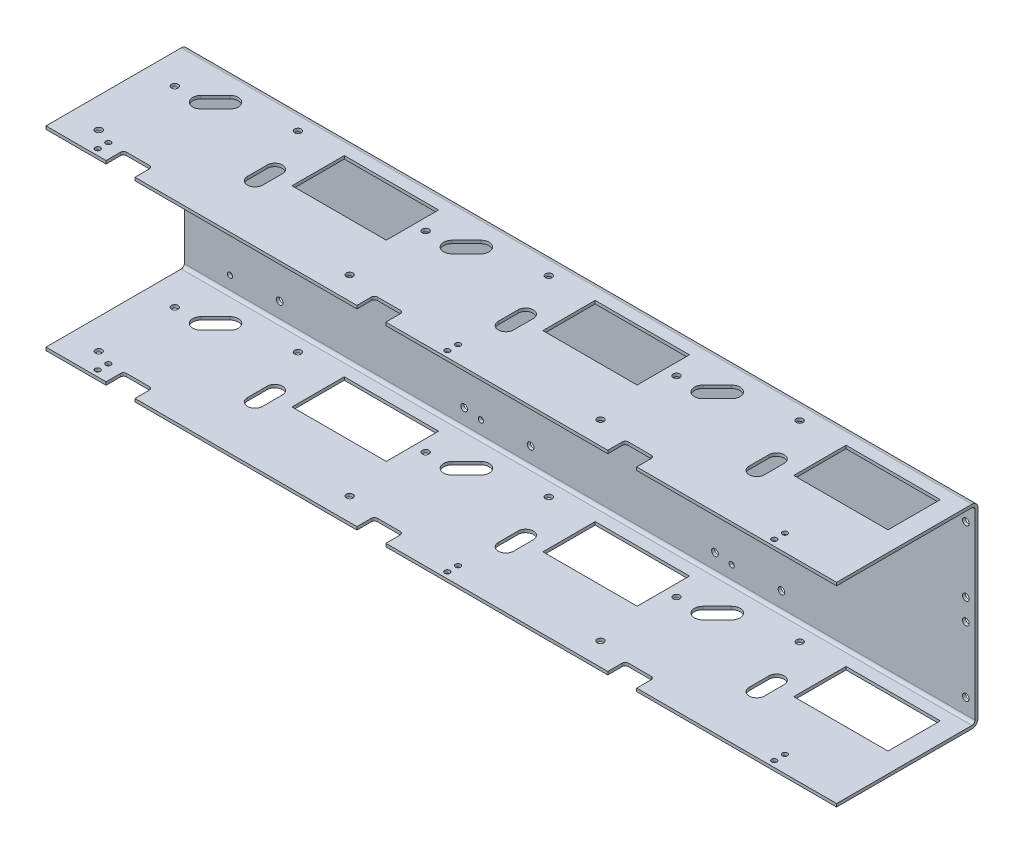
SolidWorks part; units mm, degrees
other "Bent Aluminium Chassis Tray"
ref_plane "Front Plane" through (0, 0, 0) normal (0, 0, 1) x (1, 0, 0)
ref_plane "Top Plane" through (0, 0, 0) normal (0, 1, 0) x (1, 0, 0)
ref_plane "Right Plane" through (0, 0, 0) normal (1, 0, 0) x (0, 0, -1)
sketch3d "Chassis Section Sketch datum points"
  point P0 (-285, 0, 0)
  point P1 (-285, 10, 0)
  point P2 (-285, 0, 10)
ref_plane "Chassis Section Sketch plane" through (-285, 0, 0) normal (1, 0, 0) x (0, 0, -1)
sketch "Chassis Section Sketch" plane through (-285, 0, 0) normal (1, 0, 0) x (0, 0, -1)
  line L0 (-40, -64) -> (49, -64)
  line L1 (53, -60) -> (53, 60)
  line L2 (49, 64) -> (-40, 64)
  line L3 (-40, 64) -> (-40, 62)
  line L4 (-40, 62) -> (49, 62)
  line L5 (51, 60) -> (51, -60)
  line L6 (49, -62) -> (-40, -62)
  line L7 (-40, -62) -> (-40, -64)
  arc A0 (49, -64) -> (53, -60) centre (49, -60) ccw
  arc A1 (53, 60) -> (49, 64) centre (49, 60) ccw
  arc A2 (51, 60) -> (49, 62) centre (49, 60) ccw
  arc A3 (49, -62) -> (51, -60) centre (49, -60) ccw
extrude "Chassis Section" add sketch "Chassis Section Sketch" along normal blind 520 separate body
sketch3d "Floor Mounting Holes Sketch datum points"
  point P0 (0, 0, -53.2)
  point P1 (10, 0, -53.2)
  point P2 (0, 10, -53.2)
ref_plane "Floor Mounting Holes Sketch plane" through (0, 0, -53.2) normal (0, 0, 1) x (1, 0, 0)
sketch "Floor Mounting Holes Sketch" plane through (0, 0, -53.2) normal (0, 0, 1) x (1, 0, 0)
  circle A0 centre (-255, -51.5) radius 1.7
  circle A1 centre (-222.2917, -50) radius 2.2
  circle A2 centre (-101, -50) radius 2.2
  circle A3 centre (-90, -51.5) radius 1.7
  circle A4 centre (-57.2917, -50) radius 2.2
  circle A5 centre (-222.2917, -7) radius 2.2
  circle A6 centre (-101, -7) radius 2.2
  circle A7 centre (-57.2917, -7) radius 2.2
  circle A8 centre (64, -50) radius 2.2
  circle A9 centre (75, -51.5) radius 1.7
  circle A10 centre (107.7083, -50) radius 2.2
  circle A11 centre (229, -50) radius 2.2
  circle A12 centre (64, -7) radius 2.2
  circle A13 centre (107.7083, -7) radius 2.2
  circle A14 centre (229, -7) radius 2.2
  circle A15 centre (-222.2917, 7) radius 2.2
  circle A16 centre (-101, 7) radius 2.2
  circle A17 centre (-57.2917, 7) radius 2.2
  circle A18 centre (-255, 51.5) radius 1.7
  circle A19 centre (-222.2917, 50) radius 2.2
  circle A20 centre (-101, 50) radius 2.2
  circle A21 centre (-90, 51.5) radius 1.7
  circle A22 centre (-57.2917, 50) radius 2.2
  circle A23 centre (64, 7) radius 2.2
  circle A24 centre (107.7083, 7) radius 2.2
  circle A25 centre (229, 7) radius 2.2
  circle A26 centre (64, 50) radius 2.2
  circle A27 centre (75, 51.5) radius 1.7
  circle A28 centre (107.7083, 50) radius 2.2
  circle A29 centre (229, 50) radius 2.2
extrude "Floor Mounting Holes" cut sketch "Floor Mounting Holes Sketch" along normal blind 2.4
sketch3d "Wall Openings Sketch datum points"
  point P0 (0, -65, 0)
  point P1 (10, -65, 0)
  point P2 (0, -65, 10)
ref_plane "Wall Openings Sketch plane" through (0, -65, 0) normal (0, -1, 0) x (-1, 0, 0)
sketch "Wall Openings Sketch" plane through (0, -65, 0) normal (0, -1, 0) x (-1, 0, 0)
  line L0 (170, 41.2) -> (108, 41.2)
  line L1 (108, 41.2) -> (108, 6.8)
  line L2 (108, 6.8) -> (170, 6.8)
  line L3 (170, 6.8) -> (170, 41.2)
  line L4 (180, 10.5) -> (180, -2.5)
  line L5 (190, -2.5) -> (190, 10.5)
  line L6 (243.5, -28.5) -> (228.5, -28.5)
  line L7 (226.5, -30.5) -> (226.5, -40)
  line L8 (228.5, -42) -> (243.5, -42)
  line L9 (245.5, -40) -> (245.5, -30.5)
  line L10 (251.3891, 28.3891) -> (241.8891, 37.8891)
  line L11 (234.1109, 30.1109) -> (243.6109, 20.6109)
  line L12 (5, 41.2) -> (-57, 41.2)
  line L13 (-57, 41.2) -> (-57, 6.8)
  line L14 (-57, 6.8) -> (5, 6.8)
  line L15 (5, 6.8) -> (5, 41.2)
  line L16 (15, 10.5) -> (15, -2.5)
  line L17 (25, -2.5) -> (25, 10.5)
  line L18 (78.5, -28.5) -> (63.5, -28.5)
  line L19 (61.5, -30.5) -> (61.5, -40)
  line L20 (63.5, -42) -> (78.5, -42)
  line L21 (80.5, -40) -> (80.5, -30.5)
  line L22 (86.3891, 28.3891) -> (76.8891, 37.8891)
  line L23 (69.1109, 30.1109) -> (78.6109, 20.6109)
  line L24 (-160, 41.2) -> (-222, 41.2)
  line L25 (-222, 41.2) -> (-222, 6.8)
  line L26 (-222, 6.8) -> (-160, 6.8)
  line L27 (-160, 6.8) -> (-160, 41.2)
  line L28 (-150, 10.5) -> (-150, -2.5)
  line L29 (-140, -2.5) -> (-140, 10.5)
  line L30 (-86.5, -28.5) -> (-101.5, -28.5)
  line L31 (-103.5, -30.5) -> (-103.5, -40)
  line L32 (-101.5, -42) -> (-86.5, -42)
  line L33 (-84.5, -40) -> (-84.5, -30.5)
  line L34 (-78.6109, 28.3891) -> (-88.1109, 37.8891)
  line L35 (-95.8891, 30.1109) -> (-86.3891, 20.6109)
  circle A0 centre (265.2917, 25) radius 2.2
  circle A1 centre (199.2917, 40) radius 2.2
  circle A2 centre (100.2917, 25) radius 2.2
  circle A3 centre (34.2917, 40) radius 2.2
  circle A4 centre (265.2917, -25) radius 2.2
  circle A5 centre (255, -29) radius 1.7
  circle A6 centre (255, -36) radius 1.7
  circle A7 centre (100.2917, -25) radius 2.2
  circle A8 centre (25, -29) radius 1.7
  circle A9 centre (25, -36) radius 1.7
  circle A10 centre (-64.7083, 25) radius 2.2
  circle A11 centre (-130.7083, 40) radius 2.2
  circle A12 centre (-64.7083, -25) radius 2.2
  circle A13 centre (-190, -29) radius 1.7
  circle A14 centre (-190, -36) radius 1.7
  arc A15 (180, -2.5) -> (190, -2.5) centre (185, -2.5) ccw
  arc A16 (190, 10.5) -> (180, 10.5) centre (185, 10.5) ccw
  arc A17 (245.5, -30.5) -> (243.5, -28.5) centre (243.5, -30.5) ccw
  arc A18 (228.5, -28.5) -> (226.5, -30.5) centre (228.5, -30.5) ccw
  arc A19 (226.5, -40) -> (228.5, -42) centre (228.5, -40) ccw
  arc A20 (243.5, -42) -> (245.5, -40) centre (243.5, -40) ccw
  arc A21 (241.8891, 37.8891) -> (234.1109, 30.1109) centre (238, 34) ccw
  arc A22 (243.6109, 20.6109) -> (251.3891, 28.3891) centre (247.5, 24.5) ccw
  arc A23 (15, -2.5) -> (25, -2.5) centre (20, -2.5) ccw
  arc A24 (25, 10.5) -> (15, 10.5) centre (20, 10.5) ccw
  arc A25 (80.5, -30.5) -> (78.5, -28.5) centre (78.5, -30.5) ccw
  arc A26 (63.5, -28.5) -> (61.5, -30.5) centre (63.5, -30.5) ccw
  arc A27 (61.5, -40) -> (63.5, -42) centre (63.5, -40) ccw
  arc A28 (78.5, -42) -> (80.5, -40) centre (78.5, -40) ccw
  arc A29 (76.8891, 37.8891) -> (69.1109, 30.1109) centre (73, 34) ccw
  arc A30 (78.6109, 20.6109) -> (86.3891, 28.3891) centre (82.5, 24.5) ccw
  arc A31 (-150, -2.5) -> (-140, -2.5) centre (-145, -2.5) ccw
  arc A32 (-140, 10.5) -> (-150, 10.5) centre (-145, 10.5) ccw
  arc A33 (-84.5, -30.5) -> (-86.5, -28.5) centre (-86.5, -30.5) ccw
  arc A34 (-101.5, -28.5) -> (-103.5, -30.5) centre (-101.5, -30.5) ccw
  arc A35 (-103.5, -40) -> (-101.5, -42) centre (-101.5, -40) ccw
  arc A36 (-86.5, -42) -> (-84.5, -40) centre (-86.5, -40) ccw
  arc A37 (-88.1109, 37.8891) -> (-95.8891, 30.1109) centre (-92, 34) ccw
  arc A38 (-86.3891, 20.6109) -> (-78.6109, 28.3891) centre (-82.5, 24.5) ccw
extrude "Wall Openings" cut sketch "Wall Openings Sketch" against normal blind 130
